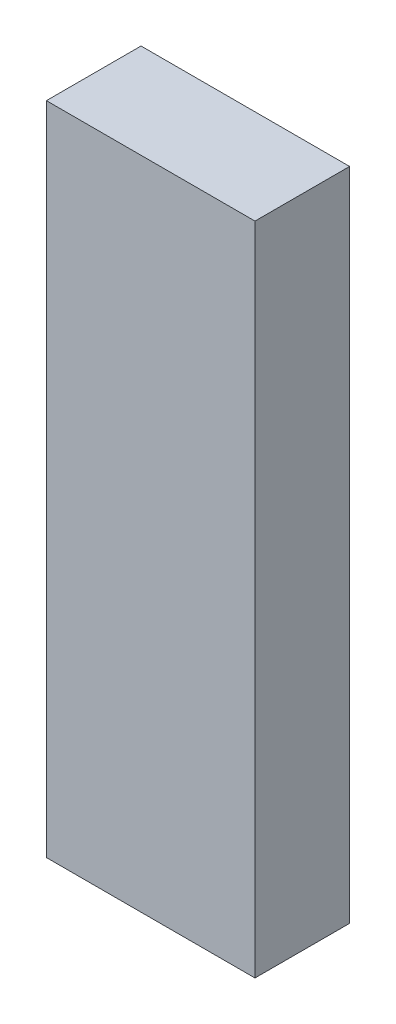
SolidWorks part; units mm, degrees
material "Pine"
ref_plane "Front Plane" through (0, 0, 0) normal (0, 0, 1) x (1, 0, 0)
ref_plane "Top Plane" through (0, 0, 0) normal (0, 1, 0) x (1, 0, 0)
ref_plane "Right Plane" through (0, 0, 0) normal (1, 0, 0) x (0, 0, -1)
sketch "Sketch1" plane through (0, 0, 0) normal (0, 1, 0) x (1, 0, 0)
  line L1 (0, 0) -> (54, 0)
  line L2 (0, 0) -> (0, 24.5)
  line L3 (0, 24.5) -> (54, 24.5)
  line L4 (54, 0) -> (54, 24.5)
  line L5 (0, 0) -> (54, 24.5) construction
  line L6 (0, 24.5) -> (54, 0) construction
  point P4 (27, 12.25)
  dimension "D1" = 24.5
  dimension "D2" = 54
extrude "Boss-Extrude1" add sketch "Sketch1" along normal blind 169.7
